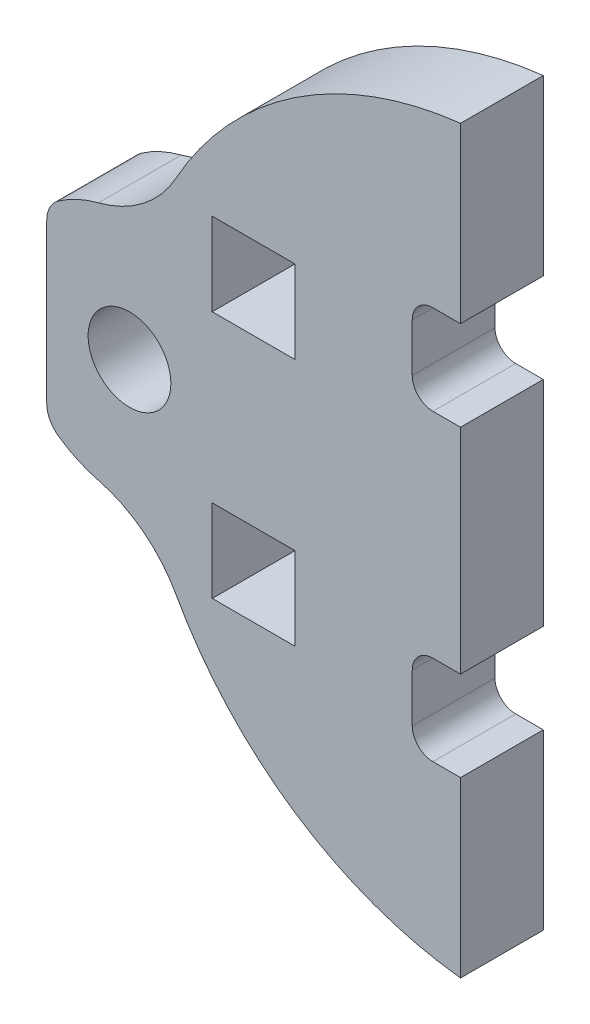
SolidWorks part; units mm, degrees
ref_plane "Alzado" through (0, 0, 0) normal (0, 0, 1) x (1, 0, 0)
ref_plane "Planta" through (0, 0, 0) normal (0, 1, 0) x (1, 0, 0)
ref_plane "Vista lateral" through (0, 0, 0) normal (1, 0, 0) x (0, 0, -1)
sketch "Model" plane through (0, 0, 0) normal (0, 0, 1) x (1, 0, 0)
  line L0 (17.668, 286.7018) -> (20.668, 286.7018)
  line L1 (17.668, 289.7018) -> (17.668, 286.7018)
  line L2 (20.668, 289.7018) -> (17.668, 289.7018)
  line L3 (20.668, 286.7018) -> (20.668, 289.7018)
  line L4 (17.668, 277.7018) -> (20.668, 277.7018)
  line L5 (17.668, 280.7018) -> (17.668, 277.7018)
  line L6 (20.668, 280.7018) -> (17.668, 280.7018)
  line L7 (20.668, 277.7018) -> (20.668, 280.7018)
  line L8 (11.668, 286.5741) -> (11.668, 280.8296)
  line L9 (26.668, 287.5768) -> (26.668, 279.8268)
  line L10 (26.668, 297.1182) -> (26.668, 290.8268)
  line L11 (26.668, 276.5768) -> (26.668, 270.2854)
  line L12 (25.668, 276.5768) -> (26.668, 276.5768)
  line L13 (24.918, 279.0768) -> (24.918, 277.3268)
  line L14 (26.668, 279.8268) -> (25.668, 279.8268)
  line L15 (25.668, 290.8268) -> (26.668, 290.8268)
  line L16 (24.918, 288.3268) -> (24.918, 290.0768)
  line L17 (26.668, 287.5768) -> (25.668, 287.5768)
  arc A0 (12.0966, 287.3948) -> (11.668, 286.5741) centre (12.668, 286.5741) ccw
  arc A1 (11.668, 280.8296) -> (12.0966, 280.0089) centre (12.668, 280.8296) ccw
  arc A2 (16.3555, 277.1662) -> (13.543, 279.3447) centre (12.418, 274.9876) ccw
  arc A3 (13.543, 288.0589) -> (16.3555, 290.2375) centre (12.418, 292.416) ccw
  arc A4 (13.543, 288.0589) -> (12.0966, 287.3948) centre (14.668, 283.7018) ccw
  circle A5 centre (14.668, 283.7018) radius 1.5
  arc A6 (24.918, 277.3268) -> (25.668, 276.5768) centre (25.668, 277.3268) ccw
  arc A7 (25.668, 279.8268) -> (24.918, 279.0768) centre (25.668, 279.0768) ccw
  arc A8 (25.668, 290.8268) -> (24.918, 290.0768) centre (25.668, 290.0768) ccw
  arc A9 (24.918, 288.3268) -> (25.668, 287.5768) centre (25.668, 288.3268) ccw
  arc A10 (16.3555, 277.1662) -> (26.668, 270.2854) centre (28.168, 283.7018) ccw
  arc A11 (12.0966, 280.0089) -> (13.543, 279.3447) centre (14.668, 283.7018) ccw
  arc A12 (26.668, 297.1182) -> (16.3555, 290.2375) centre (28.168, 283.7018) ccw
extrude "Saliente-Extruir1" add sketch "Model" along normal blind 3
